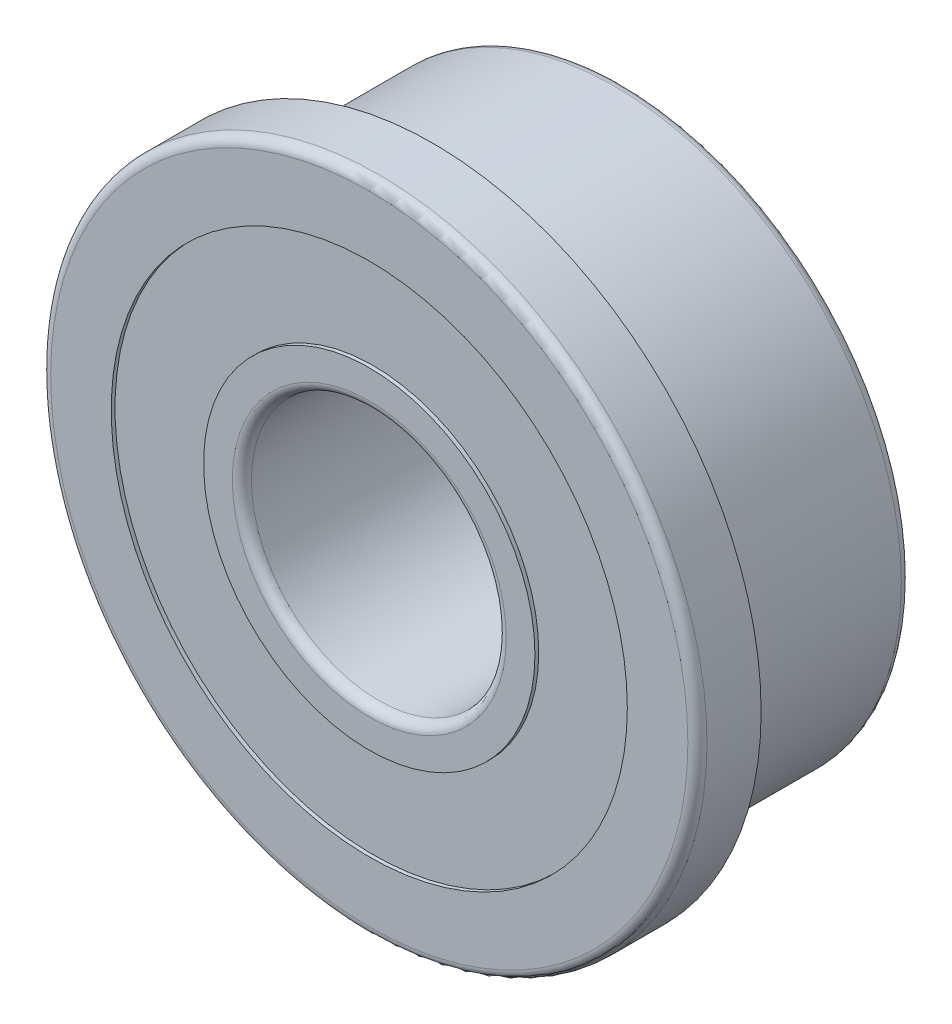
SolidWorks part; units mm, degrees
ref_plane "Front Plane" through (0, 0, 0) normal (0, 0, 1) x (1, 0, 0)
ref_plane "Top Plane" through (0, 0, 0) normal (0, 1, 0) x (1, 0, 0)
ref_plane "Right Plane" through (0, 0, 0) normal (1, 0, 0) x (0, 0, -1)
sketch "Sketch1" plane through (0, 0, 0) normal (0, 0, 1) x (1, 0, 0)
  circle A0 centre (0, 0) radius 4.5
  dimension "D1" = 9
extrude "Boss-Extrude1" add sketch "Sketch1" along normal blind 3
sketch "Sketch2" plane through (0, 0, 3) normal (0, 0, 1) x (1, 0, 0)
  circle A0 centre (0, 0) radius 5.15
  dimension "D1" = 10.3
extrude "Boss-Extrude2" add sketch "Sketch2" along normal blind 1
sketch "Sketch3" plane through (0, 0, 4) normal (0, 0, 1) x (1, 0, 0)
  circle A0 centre (0, 0) radius 2
  dimension "D1" = 4
extrude "Cut-Extrude1" cut sketch "Sketch3" against normal through all
sketch "Sketch4" plane through (0, 0, 4) normal (0, 0, 1) x (1, 0, 0)
  circle A0 centre (0, 0) radius 2.6
  circle A1 centre (0, 0) radius 4.05
  dimension "D1" = 5.2
  dimension "D2" = 8.1
extrude "Cut-Extrude2" cut sketch "Sketch4" against normal blind 0.06
sketch "Sketch5" plane through (0, 0, 0) normal (0, 0, -1) x (-1, 0, 0)
  circle A0 centre (0, 0) radius 2.6
  circle A1 centre (0, 0) radius 4.05
  dimension "D1" = 5.2
  dimension "D2" = 8.1
extrude "Cut-Extrude3" cut sketch "Sketch5" against normal blind 0.06
fillet "Fillet1" radius 0.15 4 edges at (5.15, 0, 4) (2, 0, 0) (4.5, 0, 0) (2, 0, 4)
equation "\"OD\"=9"
equation "\"D1@Sketch1\"=\"OD\""
equation "\"Flange_OD\"=10.3"
equation "\"D1@Sketch2\"=\"Flange_OD\""
equation "\"ID\"=4"
equation "\"D1@Sketch3\"=\"ID\""
